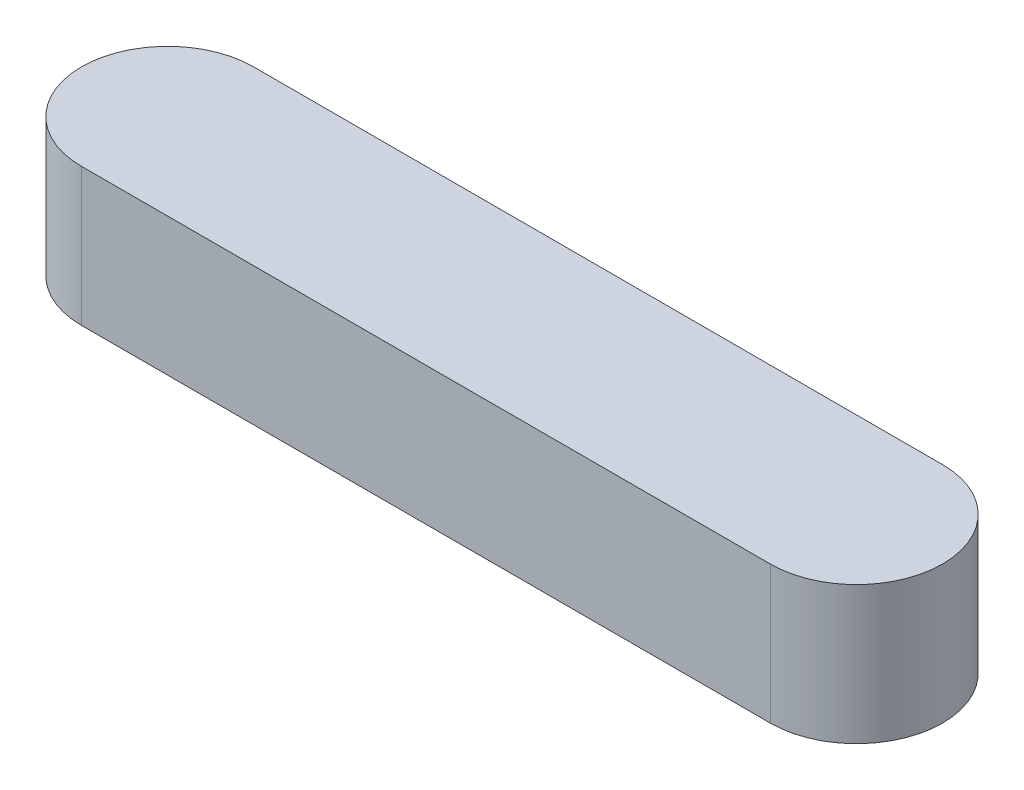
SolidWorks part; units mm, degrees
ref_plane "Front" through (0, 0, 0) normal (0, 0, 1) x (1, 0, 0)
ref_plane "Top" through (0, 0, 0) normal (0, 1, 0) x (1, 0, 0)
ref_plane "Right" through (0, 0, 0) normal (1, 0, 0) x (0, 0, -1)
sketch "support-front-body" plane through (0, 0, 0) normal (0, 0, 1) x (1, 0, 0)
  line L0 (-25, 4) -> (25, 4) construction
  line L1 (-25, 8) -> (25, 8)
  line L2 (-25, 8) -> (-25, 0)
  line L3 (-25, 0) -> (25, 0)
  line L4 (25, 8) -> (25, 0)
  line L5 (0, 8) -> (0, 0) construction
  dimension "length" = 50
  dimension "height" = 8
sketch "support-top-body" plane through (0, 0, 0) normal (0, 1, 0) x (1, 0, 0)
  line L0 (-20, 5) -> (20, 5)
  line L1 (20, -5) -> (-20, -5)
  line L2 (25, 0) -> (-25, 0) construction
  line L3 (0, 5) -> (0, -5) construction
  line L4 (-25, 0) -> (25, 0) construction
  arc A0 (20, 5) -> (20, -5) centre (20, 0) cw
  arc A1 (-20, -5) -> (-20, 5) centre (-20, 0) cw
  dimension "width" = 10
ref_plane "ref-plane-top" through (0, 8, 0) normal (0, 1, 0) x (-1, 0, 0)
sketch "Sketch4" plane through (0, 0, 0) normal (0, 1, 0) x (1, 0, 0)
  line L2 (20, 5) -> (-20, 5)
  line L3 (-20, -5) -> (20, -5)
  line L4 (20, 5) -> (-20, 5)
  line L5 (-20, -5) -> (20, -5)
  arc A2 (-20, 5) -> (-20, -5) centre (-20, 0) ccw
  arc A3 (20, -5) -> (20, 5) centre (20, 0) ccw
  arc A4 (-20, 5) -> (-20, -5) centre (-20, 0) ccw
  arc A5 (20, -5) -> (20, 5) centre (20, 0) ccw
  dimension "D1" = 0
extrude "body" add sketch "Sketch4" along normal up to surface (8 mm away) up to plane "ref-plane-top"
